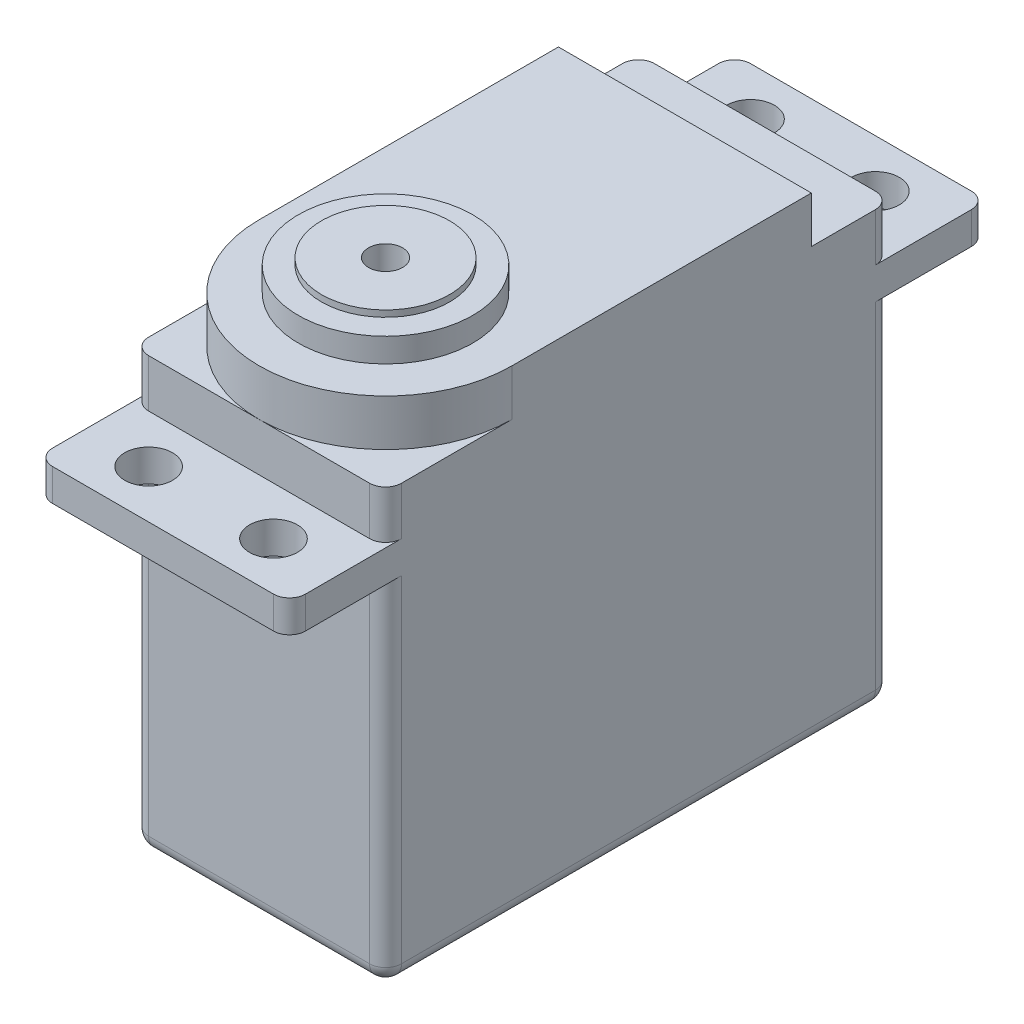
SolidWorks part; units mm, degrees
ref_plane "Front Plane" through (0, 0, 0) normal (0, 0, 1) x (1, 0, 0)
ref_plane "Top Plane" through (0, 0, 0) normal (0, 1, 0) x (1, 0, 0)
ref_plane "Right Plane" through (0, 0, 0) normal (1, 0, 0) x (0, 0, -1)
sketch "Sketch1" plane through (0, 0, 0) normal (1, 0, 0) x (0, 0, -1)
  line L1 (0, 0) -> (40.132, 0)
  line L2 (0, 0) -> (0, 34.29)
  line L3 (0, 34.29) -> (40.132, 34.29)
  line L4 (40.132, 0) -> (40.132, 34.29)
  dimension "D1" = 40.132
  dimension "D2" = 34.29
extrude "Boss-Extrude1" add sketch "Sketch1" along normal blind 20.066
sketch "Sketch2" plane through (0, 34.29, 0) normal (0, 1, 0) x (1, 0, 0)
  line L0 (0, 40.132) -> (0, 0) construction
  line L1 (0, 33.782) -> (20.066, 33.782)
  line L2 (0, 33.782) -> (0, 10.033)
  line L3 (20.066, 40.132) -> (0, 40.132) construction
  line L4 (20.066, 33.782) -> (20.066, 10.033)
  line L5 (20.066, 40.132) -> (20.066, 0) construction
  line L6 (20.066, 0) -> (0, 0) construction
  arc A0 (0, 10.033) -> (20.066, 10.033) centre (10.033, 10.033) ccw
  dimension "D1" = 6.35
  dimension "D2" = 10.033
  dimension "D3" = 10.033
extrude "Boss-Extrude2" add sketch "Sketch2" along normal blind 3.683
sketch "Sketch3" plane through (0, 37.973, 0) normal (0, 1, 0) x (1, 0, 0)
  circle A0 centre (10.033, 10.033) radius 6.9215
  dimension "D1" = 13.843
extrude "Boss-Extrude3" add sketch "Sketch3" along normal blind 1.905
sketch "Sketch4" plane through (0, 39.878, 0) normal (0, 1, 0) x (1, 0, 0)
  circle A0 centre (10.033, 10.033) radius 5.08
  dimension "D1" = 10.16
extrude "Boss-Extrude4" add sketch "Sketch4" along normal blind 0.508
hole_wizard "#6-32 Tapped Hole1" positions "Sketch6" profile "Sketch7" tap size "#6-32" standard "ANSI Inch"
sketch "Sketch6" plane through (0, 40.386, 0) normal (0, 1, 0) x (1, 0, 0)
  point P0 (10.033, 10.033)
sketch "Sketch7" plane through (10.033, 40.386, -10.033) normal (1, 0, 0) x (0, 0, 1)
  line L0 (0, 0) -> (0, 11.9887)
  line L1 (0, 11.9887) -> (1.3525, 11.176)
  line L2 (1.3525, 11.176) -> (1.3525, 0)
  line L5 (1.3525, 0) -> (0, 0)
  line L10 (0, 11.9887) -> (-1.3525, 11.176) construction
  line L11 (0, -6.35) -> (0, 107.95) construction
  dimension "Tap Drill Dia." = 2.7051
  dimension "Tap Drill Depth" = 11.176
  dimension "Drill Angle" = 118
cosmetic thread "Hole Thread1" parameters "D1"=7.112, "D2"=3.5052
sketch "Sketch8" plane through (0, 0, 0) normal (0, 0, 1) x (1, 0, 0)
  line L0 (20.066, 34.29) -> (20.066, 0) construction
  line L1 (20.066, 30.48) -> (0, 30.48)
  line L2 (20.066, 30.48) -> (20.066, 27.94)
  line L3 (20.066, 27.94) -> (0, 27.94)
  line L4 (0, 30.48) -> (0, 27.94)
  line L5 (0, 34.29) -> (0, 0) construction
  line L6 (10.033, 34.29) -> (0, 34.29) construction
  dimension "D1" = 3.81
  dimension "D2" = 2.54
extrude "Boss-Extrude5" add sketch "Sketch8" along normal blind 7.62
sketch "Sketch9" plane through (0, 0, -40.132) normal (0, 0, -1) x (-1, 0, 0)
  line L0 (-20.066, 0) -> (-20.066, 34.29) construction
  line L1 (-20.066, 30.48) -> (0, 30.48)
  line L2 (-20.066, 30.48) -> (-20.066, 27.94)
  line L3 (-20.066, 27.94) -> (0, 27.94)
  line L4 (0, 30.48) -> (0, 27.94)
  line L5 (0, 0) -> (0, 34.29) construction
  line L6 (-20.066, 34.29) -> (0, 34.29) construction
  dimension "D1" = 3.81
  dimension "D2" = 2.54
extrude "Boss-Extrude6" add sketch "Sketch9" along normal blind 7.62
hole_wizard "#6 Clearance Hole1" positions "Sketch11" profile "Sketch10" hole size "#6" standard "ANSI Inch"
sketch "Sketch11" plane through (0, 30.48, 0) normal (0, 1, 0) x (1, 0, 0)
  line L0 (20.066, -7.62) -> (20.066, 0) construction
  line L1 (0, -7.62) -> (0, 0) construction
  line L2 (0, 47.752) -> (0, 40.132) construction
  line L3 (20.066, 47.752) -> (20.066, 40.132) construction
  line L4 (20.066, 0) -> (0, 0) construction
  line L5 (0, 40.132) -> (20.066, 40.132) construction
  point P0 (14.986, -3.81)
  point P2 (5.08, -3.81)
  point P4 (5.08, 43.942)
  point P6 (14.986, 43.942)
  dimension "D1" = 5.08
  dimension "D2" = 5.08
  dimension "D3" = 5.08
  dimension "D4" = 5.08
  dimension "D5" = 3.81
  dimension "D6" = 3.81
  dimension "D7" = 3.81
  dimension "D8" = 3.81
sketch "Sketch10" plane through (14.986, 30.48, 3.81) normal (1, 0, 0) x (0, 0, 1)
  line L0 (0, 0) -> (0, 4.9508)
  line L1 (0, 4.9508) -> (1.8986, 3.81)
  line L2 (1.8986, 3.81) -> (1.8986, 0)
  line L5 (1.8986, 0) -> (0, 0)
  line L10 (0, 4.9508) -> (-1.8986, 3.81) construction
  line L11 (0, -6.35) -> (0, 107.95) construction
  dimension "Hole Dia." = 3.7973
  dimension "Hole Depth" = 3.81
  dimension "Drill Angle" = 118
fillet "Fillet1" radius 1.27 16 edges at (10.033, 0, 0) (20.066, 0, -20.066) (10.033, 0, -40.132) (0, 0, -20.066) (20.066, 32.385, 0) (20.066, 13.97, 0) (0, 32.385, 0) (0, 13.97, 0) (20.066, 29.21, -47.752) (0, 29.21, -47.752) (20.066, 29.21, 7.62) (0, 29.21, 7.62)
